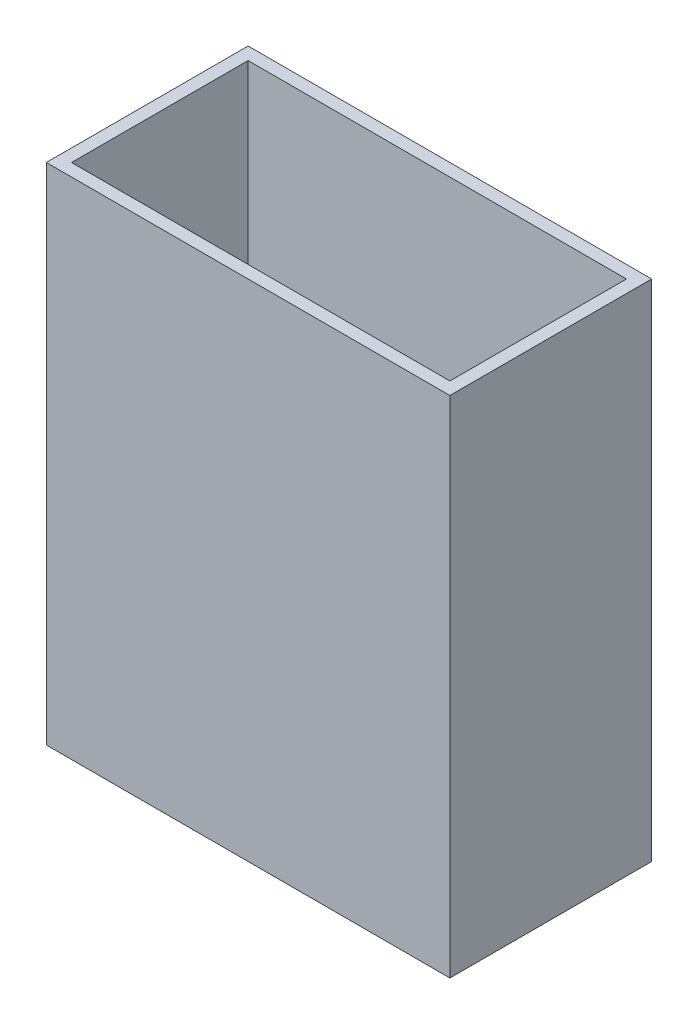
SolidWorks part; units mm, degrees
ref_plane "Front Plane" through (0, 0, 0) normal (0, 0, 1) x (1, 0, 0)
ref_plane "Top Plane" through (0, 0, 0) normal (0, 1, 0) x (1, 0, 0)
ref_plane "Right Plane" through (0, 0, 0) normal (1, 0, 0) x (0, 0, -1)
sketch "Sketch1" plane through (0, 0, 0) normal (0, 1, 0) x (1, 0, 0)
  line L1 (-80, 40) -> (80, 40)
  line L2 (-80, 40) -> (-80, -40)
  line L3 (-80, -40) -> (80, -40)
  line L4 (80, 40) -> (80, -40)
  line L5 (-80, 40) -> (80, -40) construction
  line L6 (-80, -40) -> (80, 40) construction
  point P0 (0, 0)
  dimension "D1" = 80
  dimension "D2" = 160
extrude "Boss-Extrude1" add sketch "Sketch1" along normal blind 225
sketch "Sketch2" plane through (0, 225, 0) normal (0, 1, 0) x (1, 0, 0)
  line L1 (-75, 35) -> (75, 35)
  line L2 (-75, 35) -> (-75, -35)
  line L3 (-75, -35) -> (75, -35)
  line L4 (75, 35) -> (75, -35)
  line L5 (-75, 35) -> (75, -35) construction
  line L6 (-75, -35) -> (75, 35) construction
  point P0 (0, 0)
  dimension "D1" = 150
  dimension "D2" = 70
extrude "Cut-Extrude1" cut sketch "Sketch2" against normal blind 220
sketch "Sketch7" plane through (0, 0, 35) normal (0, 0, -1) x (-1, 0, 0)
  line L0 (-80, 225) -> (-80, 0) construction
  line L1 (-40.5, 125) -> (-34.5, 125)
  line L2 (-40.5, 125) -> (-40.5, 5)
  line L3 (-40.5, 5) -> (-34.5, 5)
  line L4 (-34.5, 125) -> (-34.5, 5)
  line L5 (-40.5, 125) -> (-34.5, 5) construction
  line L6 (-40.5, 5) -> (-34.5, 125) construction
  line L7 (0, -8.2288) -> (0, 17.5288) construction
  line L8 (40.5, 5) -> (34.5, 5)
  line L9 (34.5, 125) -> (34.5, 5)
  line L10 (40.5, 125) -> (40.5, 5)
  line L11 (40.5, 125) -> (34.5, 125)
  line L12 (-3, 125) -> (-3, 5)
  line L13 (-3, 125) -> (3, 125)
  line L14 (3, 125) -> (3, 5)
  line L15 (-3, 5) -> (3, 5)
  line L16 (-1, 125) -> (-1, 5)
  line L17 (-38.5, 125) -> (-36.5, 125)
  line L18 (-38.5, 125) -> (-38.5, 5)
  line L19 (-38.5, 5) -> (-36.5, 5)
  line L20 (-36.5, 125) -> (-36.5, 5)
  line L21 (-38.5, 125) -> (-36.5, 5) construction
  line L22 (-38.5, 5) -> (-36.5, 125) construction
  line L23 (-1, 125) -> (1, 125)
  line L24 (1, 125) -> (1, 5)
  line L25 (-1, 5) -> (1, 5)
  line L26 (36.5, 125) -> (36.5, 5)
  line L27 (38.5, 125) -> (38.5, 5)
  line L28 (-80, 0) -> (80, 0) construction
  point P0 (-37.5, 65)
  point P15 (-37.5, 65)
  point P33 (0, 0)
  point P34 (0, 0)
  dimension "D1" = 6
  dimension "D2" = 120
  dimension "D3" = 42.5
  dimension "D5" = 120
  dimension "D6" = 2
  dimension "D7" = 2
  dimension "D8" = 5
  dimension "D9" = 31.5
  dimension "D10" = 2
  dimension "D4" = 2
extrude "Boss-Extrude2" add sketch "Sketch7" along normal blind 5 contours L18 L1 L2 L3 | L1 L20 L3 L4 | L16 L13 L12 L15 | L13 L24 L15 L14 | L26 L11 L9 L8 | L11 L27 L8 L10
sketch "Sketch8" plane through (0, 0, -35) normal (0, 0, 1) x (1, 0, 0)
  line L0 (-80, 0) -> (80, 0) construction
  line L1 (-38.5, 125) -> (-36.5, 125)
  line L2 (-38.5, 125) -> (-38.5, 5)
  line L3 (-38.5, 5) -> (-36.5, 5)
  line L4 (-36.5, 125) -> (-36.5, 5)
  line L5 (-38.5, 125) -> (-36.5, 5) construction
  line L6 (-38.5, 5) -> (-36.5, 125) construction
  line L7 (-40.5, 125) -> (-34.5, 125)
  line L8 (-40.5, 125) -> (-40.5, 5)
  line L9 (-40.5, 5) -> (-34.5, 5)
  line L10 (-34.5, 125) -> (-34.5, 5)
  line L11 (-40.5, 125) -> (-34.5, 5) construction
  line L12 (-40.5, 5) -> (-34.5, 125) construction
  line L13 (0, 0) -> (0, 25.2888) construction
  line L14 (38.5, 125) -> (36.5, 125)
  line L15 (40.5, 125) -> (34.5, 125)
  line L16 (40.5, 5) -> (34.5, 5)
  line L17 (38.5, 5) -> (36.5, 5)
  line L18 (34.5, 125) -> (34.5, 5)
  line L19 (36.5, 125) -> (36.5, 5)
  line L20 (38.5, 125) -> (38.5, 5)
  line L21 (40.5, 125) -> (40.5, 5)
  line L22 (-3, 125) -> (-3, 5)
  line L23 (-3, 125) -> (3, 125)
  line L24 (3, 125) -> (3, 5)
  line L25 (-3, 5) -> (3, 5)
  line L26 (-1, 125) -> (-1, 5)
  line L27 (-1, 125) -> (1, 125)
  line L28 (1, 125) -> (1, 5)
  line L29 (-1, 5) -> (1, 5)
  line L33 (-80, 225) -> (-80, 0) construction
  point P0 (-37.5, 65)
  point P5 (-37.5, 65)
  line M22 (-75, 5) -> (75, 5)
  dimension "D1" = 120
  dimension "D2" = 5
  dimension "D3" = 2
  dimension "D4" = 6
  dimension "D6" = 42.5
  dimension "D7" = 31.5
  dimension "D5" = 2
extrude "Boss-Extrude3" add sketch "Sketch8" along normal blind 5 contours L7 L8 L2 M22 | L10 L7 L4 M22 | L26 L23 L22 M22 | L23 L28 L24 M22 | L19 L15 L18 M22 | L21 L15 L20 M22
sketch "Sketch9" plane through (-75, 0, 0) normal (1, 0, 0) x (0, 0, -1)
  line L0 (-40, 0) -> (40, 0) construction
  line L1 (-3, 125) -> (3, 125)
  line L2 (-3, 125) -> (-3, 5)
  line L3 (-3, 5) -> (3, 5)
  line L4 (3, 125) -> (3, 5)
  line L5 (-3, 125) -> (3, 5) construction
  line L6 (-3, 5) -> (3, 125) construction
  line L7 (-40, 225) -> (-40, 0) construction
  line L9 (-1, 125) -> (1, 125)
  line L10 (-1, 125) -> (-1, 5)
  line L11 (-1, 5) -> (1, 5)
  line L12 (1, 125) -> (1, 5)
  line L13 (-1, 125) -> (1, 5) construction
  line L14 (-1, 5) -> (1, 125) construction
  point P0 (0, 65)
  point P7 (0, 65)
  line M7 (-35, 5) -> (35, 5)
  dimension "D1" = 6
  dimension "D2" = 120
  dimension "D3" = 65
  dimension "D4" = 40
  dimension "D5" = 2
  dimension "D6" = 120
extrude "Boss-Extrude4" add sketch "Sketch9" along normal blind 5 contours L10 L1 L2 M7 | L1 L12 L4 M7
sketch "Sketch10" plane through (75, 0, 0) normal (-1, 0, 0) x (0, 0, 1)
  line L0 (-40, 0) -> (40, 0) construction
  line L1 (-3, 125) -> (3, 125)
  line L2 (-3, 125) -> (-3, 5)
  line L3 (-3, 5) -> (3, 5)
  line L4 (3, 125) -> (3, 5)
  line L5 (-3, 125) -> (3, 5) construction
  line L6 (-3, 5) -> (3, 125) construction
  line L7 (-40, 225) -> (-40, 0) construction
  line L9 (-1, 125) -> (1, 125)
  line L10 (-1, 125) -> (-1, 5)
  line L11 (-1, 5) -> (1, 5)
  line L12 (1, 125) -> (1, 5)
  line L13 (-1, 125) -> (1, 5) construction
  line L14 (-1, 5) -> (1, 125) construction
  point P0 (0, 65)
  point P9 (0, 65)
  line M6 (-35, 5) -> (35, 5)
  dimension "D1" = 120
  dimension "D2" = 6
  dimension "D3" = 5
  dimension "D4" = 40
  dimension "D5" = 2
extrude "Boss-Extrude5" add sketch "Sketch10" along normal blind 5 contours L10 L1 L2 M6 | L1 L12 L4 M6
sketch "Sketch11" plane through (0, 225, 0) normal (0, 1, 0) x (1, 0, 0)
  line L1 (-80, 40) -> (80, 40)
  line L2 (-80, 40) -> (-80, -40)
  line L3 (-80, -40) -> (80, -40)
  line L4 (80, 40) -> (80, -40)
  line L5 (-75, 35) -> (75, 35)
  line L6 (-75, 35) -> (-75, -35)
  line L7 (-75, -35) -> (75, -35)
  line L8 (75, 35) -> (75, -35)
extrude "Cut-Extrude2" cut sketch "Sketch11" against normal blind 25 contours L2 L1 L4 L3 | L6 L5 L8 L7
